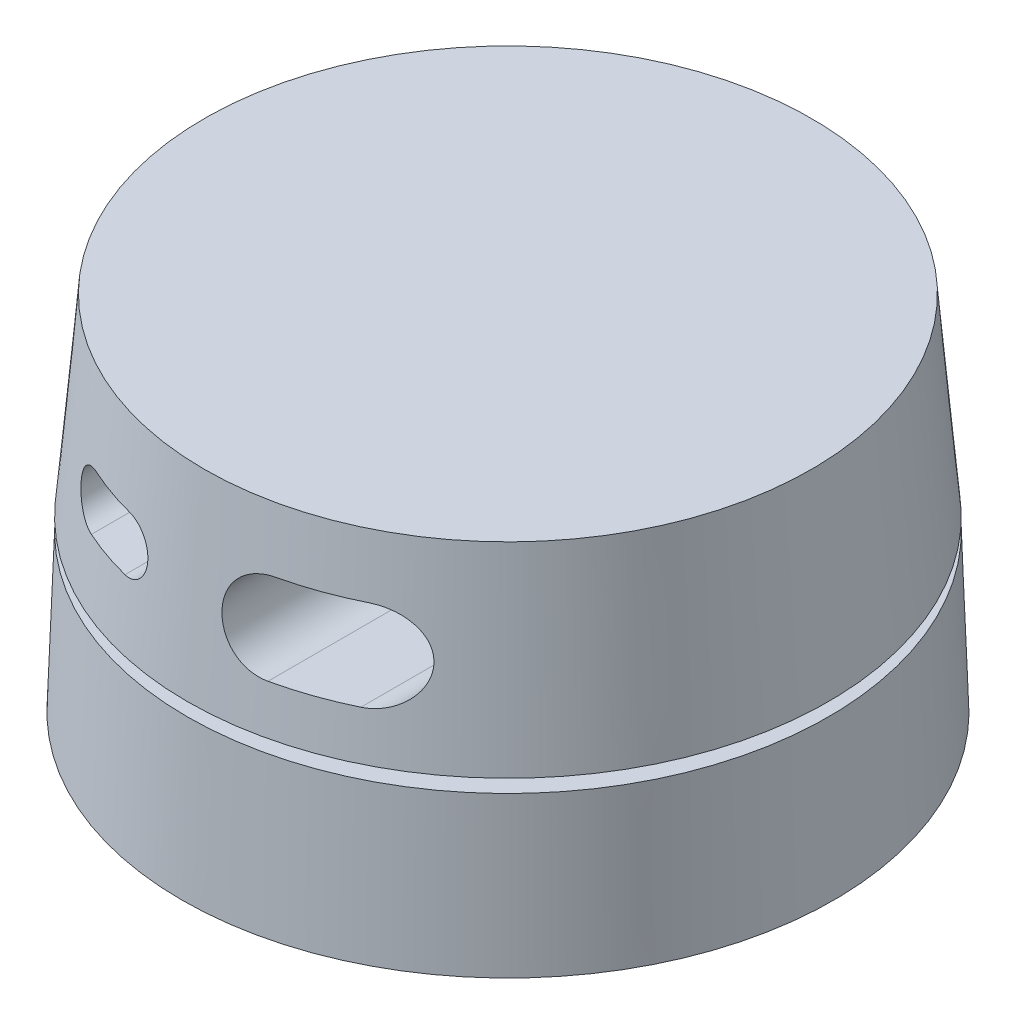
SolidWorks part; units mm, degrees
material "1060 合金"
ref_plane "前视基准面" through (0, 0, 0) normal (0, 0, 1) x (1, 0, 0)
ref_plane "上视基准面" through (0, 0, 0) normal (0, 1, 0) x (1, 0, 0)
ref_plane "右视基准面" through (0, 0, 0) normal (1, 0, 0) x (0, 0, -1)
sketch "草图1" plane through (0, 0, 0) normal (0, 1, 0) x (1, 0, 0)
  circle A0 centre (0, 0) radius 37.83
  dimension "D1" = 75.66
extrude "凸台-拉伸1" add sketch "草图1" along normal blind 18.1
draft "拔模1" type of draft neutral plane draft angle 2 faces to draft 1 face at (0, 18.1, 37.83) neutral plane through (0, 0, 0) neutral plane normal (0, -1, 0) reverse direction yes parameters "D1"=2
sketch "草图3" plane through (0, 18.1, 0) normal (0, 1, 0) x (1, 0, 0)
  circle A0 centre (0, 0) radius 34
  dimension "D1" = 68
extrude "凸台-拉伸2" add sketch "草图3" along normal blind 1.53
sketch "草图4" plane through (0, 19.63, 0) normal (0, 1, 0) x (1, 0, 0)
  circle A0 centre (0, 0) radius 37.1979
extrude "凸台-拉伸3" add sketch "草图4" along normal blind 22.37
draft "拔模2" type of draft neutral plane draft angle 5 faces to draft 1 face at (0, 42, 37.1979) neutral plane through (0, 19.63, 0) neutral plane normal (0, -1, 0) reverse direction yes parameters "D1"=5
sketch "草图5" plane through (0, 0, 0) normal (0, -1, 0) x (1, 0, 0)
  line L0 (0, 0) -> (65.8215, 0) construction
  line L1 (0, 0) -> (0, 36.6548) construction
  circle A0 centre (29, 0) radius 1.5
  circle A1 centre (-29, 0) radius 1.5
  circle A2 centre (0, 29) radius 1.5
  circle A3 centre (0, -29) radius 1.5
  dimension "D1" = 3
  dimension "D2" = 58
  dimension "D3" = 3
  dimension "D4" = 58
extrude "切除-拉伸1" cut sketch "草图5" against normal blind 10
ref_plane "基准面5" through (0, 0, 40) normal (0, 0, 1) x (1, 0, 0)
sketch "草图6" plane through (0, 0, 40) normal (0, 0, 1) x (1, 0, 0)
  line L0 (0, 0) -> (0, 51.1774) construction
  line L1 (0, 30) -> (29.8658, 30) construction
  line L2 (-37.83, 0) -> (37.83, 0) construction
  line L3 (8, 30) -> (16, 30) construction
  line L4 (8, 35) -> (16, 35)
  line L5 (8, 25) -> (16, 25)
  line L6 (-15, 30) -> (-9, 30) construction
  line L7 (-15, 33) -> (-9, 33)
  line L8 (-15, 27) -> (-9, 27)
  arc A0 (8, 35) -> (8, 25) centre (8, 30) ccw
  arc A1 (16, 25) -> (16, 35) centre (16, 30) ccw
  arc A2 (-15, 33) -> (-15, 27) centre (-15, 30) ccw
  arc A3 (-9, 27) -> (-9, 33) centre (-9, 30) ccw
  point P9 (12, 30)
  point P16 (-12, 30)
  dimension "D2" = 5
  dimension "D6" = 3
  dimension "D1" = 30
  dimension "D3" = 12
  dimension "D4" = 8
  dimension "D5" = 6
  dimension "D7" = 12
extrude "切除-拉伸2" cut sketch "草图6" against normal blind 30
